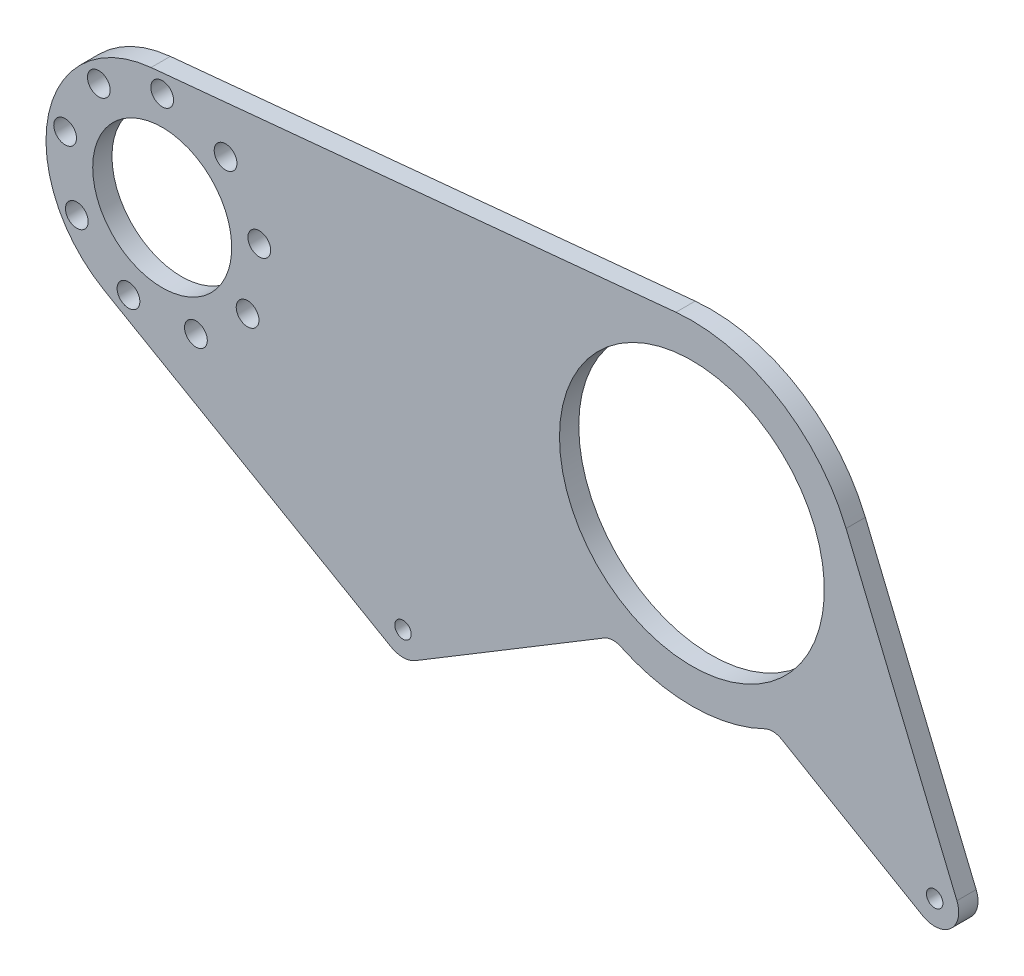
SolidWorks part; units mm, degrees
ref_plane "Front Plane" through (0, 0, 0) normal (0, 0, 1) x (1, 0, 0)
ref_plane "Top Plane" through (0, 0, 0) normal (0, 1, 0) x (1, 0, 0)
ref_plane "Right Plane" through (0, 0, 0) normal (1, 0, 0) x (0, 0, -1)
sketch "Sketch1" plane through (0, 0, 0) normal (0, 0, 1) x (1, 0, 0)
  line L0 (-328.2524, 147.3627) -> (-120.6238, 167.3365)
  line L1 (-346.8169, 61.7737) -> (-233.3583, -3.6551)
  line L2 (-223.6766, -3.5577) -> (-149.0272, 41.5159)
  line L3 (-114.3, 88.9) -> (-114.3, 101.6) construction
  line L4 (-53.3056, 126.9173) -> (-9.4675, 21.3025)
  line L5 (-23.0618, 9.4221) -> (-78.8665, 41.9532)
  line L6 (-1014.6252, 165.6604) -> (-1019.8901, 160.3955)
  line L7 (-1030.9863, 164.9917) -> (-1030.9863, 171.5644)
  line L8 (-1044.6639, 171.5644) -> (-1044.6639, 164.9917)
  line L9 (-1057.6639, 164.9917) -> (-1057.6639, 165.5687)
  line L10 (-969.3772, 190.4868) -> (-969.3772, 65.9625) construction
  line L11 (-881.0905, 164.9917) -> (-881.0905, 165.5687)
  line L12 (-894.0905, 171.5644) -> (-894.0905, 164.9917)
  line L13 (-907.768, 164.9917) -> (-907.768, 171.5644)
  line L14 (-924.1291, 165.6604) -> (-918.8642, 160.3955)
  line L15 (-323.85, 101.6) -> (-323.85, 140.5992) construction
  circle A0 centre (-114.3, 88.9) radius 82.9716 construction
  circle A1 centre (-228.6, -20.8038) radius 12.7 construction
  circle A2 centre (0, 0) radius 12.7 construction
  circle A3 centre (-323.85, 101.6) radius 114 construction
  circle A5 centre (-114.3, 101.6) radius 52.3875
  arc A6 (-142.4404, 41.8555) -> (-85.4371, 42.2012) centre (-114.3, 101.6) ccw
  arc A8 (-223.6766, -3.5577) -> (-233.3583, -3.6551) centre (-228.6, 4.5962) cw
  arc A9 (-9.4675, 21.3025) -> (-23.0618, 9.4221) centre (-18.2648, 17.651) cw
  circle A10 centre (-228.6, 4.5962) radius 3.2512
  circle A11 centre (-18.2648, 17.651) radius 3.2512
  arc A12 (-142.4404, 41.8555) -> (-149.0272, 41.5159) centre (-145.4168, 35.5364) ccw
  arc A13 (-78.8665, 41.9532) -> (-85.4371, 42.2012) centre (-82.3843, 35.9187) ccw
  circle A14 centre (-114.3, 101.6) radius 66.04 construction
  arc A15 (-120.6238, 167.3365) -> (-53.3056, 126.9173) centre (-114.3, 101.6) cw
  arc A16 (-1060.2851, 168.1074) -> (-1057.6639, 165.5687) centre (-1060.2039, 165.5687) cw
  arc A17 (-1011.3674, 165.9415) -> (-1004.7193, 96.4436) centre (-1037.8251, 128.3437) cw
  arc A18 (-1061.5126, 167.7456) -> (-1011.3674, 165.9415) centre (-1037.8251, 128.3437) ccw construction
  arc A19 (-1011.3674, 165.9415) -> (-1014.6252, 165.6604) centre (-1012.8292, 163.8643) ccw
  arc A20 (-1030.9863, 164.9917) -> (-1019.8901, 160.3955) centre (-1024.4863, 164.9917) ccw
  arc A21 (-1030.9863, 171.5644) -> (-1033.2749, 174.0919) centre (-1033.5263, 171.5644) ccw
  arc A22 (-1033.2749, 174.0919) -> (-1042.3753, 174.0919) centre (-1037.8251, 128.3437) ccw
  arc A23 (-1042.3753, 174.0919) -> (-1044.6639, 171.5644) centre (-1042.1239, 171.5644) ccw
  arc A24 (-1057.6639, 164.9917) -> (-1044.6639, 164.9917) centre (-1051.1639, 164.9917) ccw
  arc A25 (-1057.6639, 165.5687) -> (-1061.5126, 167.7456) centre (-1060.2039, 165.5687) ccw construction
  circle A26 centre (-1037.8251, 167.3437) radius 4.5
  circle A27 centre (-1037.8251, 128.3437) radius 27.4955
  arc A28 (-881.0905, 165.5687) -> (-877.2418, 167.7456) centre (-878.5505, 165.5687) cw construction
  arc A29 (-877.2418, 167.7456) -> (-927.3869, 165.9415) centre (-900.9293, 128.3437) cw construction
  circle A30 centre (-900.9293, 128.3437) radius 27.4955
  circle A31 centre (-900.9293, 167.3437) radius 4.5
  arc A32 (-881.0905, 164.9917) -> (-894.0905, 164.9917) centre (-887.5905, 164.9917) cw
  arc A33 (-896.3791, 174.0919) -> (-894.0905, 171.5644) centre (-896.6305, 171.5644) cw
  arc A34 (-905.4794, 174.0919) -> (-896.3791, 174.0919) centre (-900.9293, 128.3437) cw
  arc A35 (-907.768, 171.5644) -> (-905.4794, 174.0919) centre (-905.228, 171.5644) cw
  arc A36 (-907.768, 164.9917) -> (-918.8642, 160.3955) centre (-914.268, 164.9917) cw
  arc A37 (-927.3869, 165.9415) -> (-924.1291, 165.6604) centre (-925.9252, 163.8643) cw
  arc A38 (-927.3869, 165.9415) -> (-934.035, 96.4436) centre (-900.9293, 128.3437) ccw
  arc A39 (-878.4693, 168.1074) -> (-881.0905, 165.5687) centre (-878.5505, 165.5687) ccw
  circle A40 centre (-323.85, 101.6) radius 45.974 construction
  circle A41 centre (-323.85, 140.5992) radius 4.4996
  circle A42 centre (-298.7818, 131.4751) radius 4.4996
  circle A43 centre (-285.4433, 108.3721) radius 4.4996
  circle A44 centre (-290.0757, 82.1004) radius 4.4996
  circle A45 centre (-310.5115, 64.9528) radius 4.4996
  circle A46 centre (-337.1885, 64.9528) radius 4.4996
  circle A47 centre (-357.6243, 82.1004) radius 4.4996
  circle A48 centre (-362.2567, 108.3721) radius 4.4996
  circle A49 centre (-348.9182, 131.4751) radius 4.4996
  arc A50 (-328.2524, 147.3627) -> (-346.8169, 61.7737) centre (-323.85, 101.6) ccw
  circle A51 centre (-323.85, 101.6) radius 27.4955
  point P107 (-323.85, 101.6)
  dimension "D1" = 25.4
  dimension "D2" = 25.4
  dimension "D7" = 165.9433
  dimension "D8" = 228
  dimension "D9" = 54.991
  dimension "D11" = 104.775
  dimension "D14" = 132.08
  dimension "D15" = 9
  dimension "D16" = 9.525
  dimension "D18" = 9.525
  dimension "D20" = 6.5024
  dimension "D21" = 6.5024
  dimension "D23" = 6.985
  dimension "D24" = 6.985
  dimension "D25" = 66.04
  dimension "D26" = 2.54
  dimension "D27" = 6.5
  dimension "D28" = 91.948
  dimension "D30" = 8.9992
  dimension "D32" = 54.991
  dimension "D3" = 228.6
  dimension "D4" = 20.8038
  dimension "D5" = 88.9
  dimension "D6" = 114.3
  dimension "D10" = 12.7
  dimension "D12" = 12.7
  dimension "D13" = 209.55
  dimension "D17" = 25.4
  dimension "D19" = 25.4
  dimension "D22" = 17.651
  dimension "D29" = 38.9992
  dimension "D31" = 9
extrude "Boss-Extrude1" add sketch "Sketch1" along normal blind 7.62 contours L0 A50 L1 A8 L2 A12 A6 A13 L5 A9 L4 A15 A51 A5 A10 A11 A41 A42 A43 A44 A45 A46 A47 A48 A49
